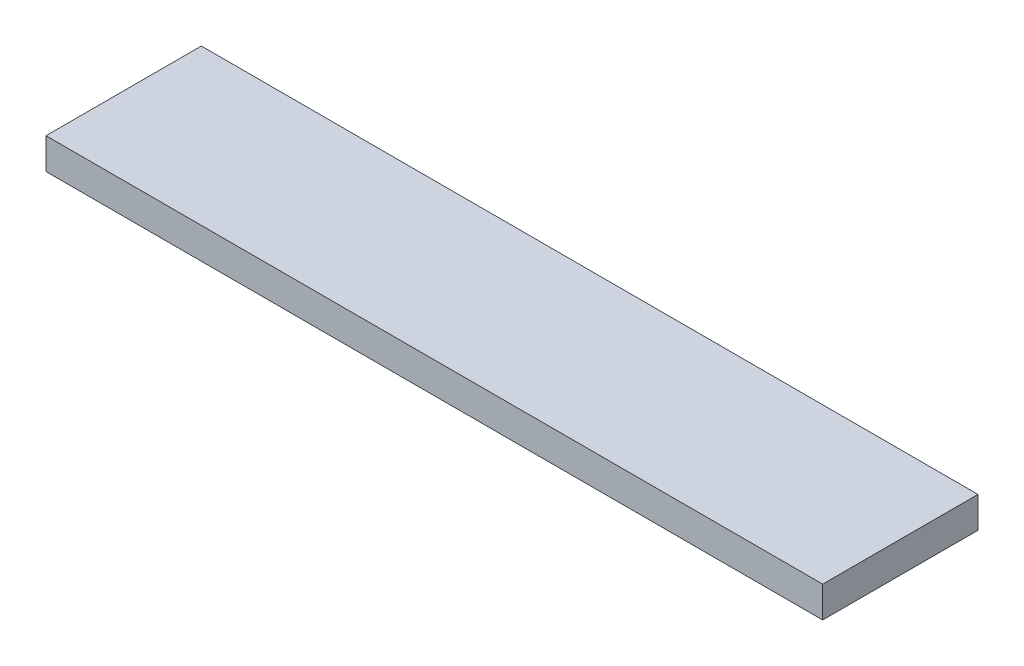
SolidWorks part; units mm, degrees
ref_plane "Plan de face" through (0, 0, 0) normal (0, 0, 1) x (1, 0, 0)
ref_plane "Plan de dessus" through (0, 0, 0) normal (0, 1, 0) x (1, 0, 0)
ref_plane "Plan de droite" through (0, 0, 0) normal (1, 0, 0) x (0, 0, -1)
sketch "Esquisse1" plane through (0, 0, 0) normal (0, 0, 1) x (1, 0, 0)
  line L0 (-25, 1) -> (25, 1)
  line L1 (25, 1) -> (25, -1)
  line L2 (25, -1) -> (-25, -1)
  line L3 (-25, -1) -> (-25, 1)
  line L4 (25, 1) -> (-25, -1) construction
  point P2 (0, 0)
  dimension "D1" = 50
  dimension "D2" = 2
extrude "Boss.-Extru.1" add sketch "Esquisse1" along normal blind 10
